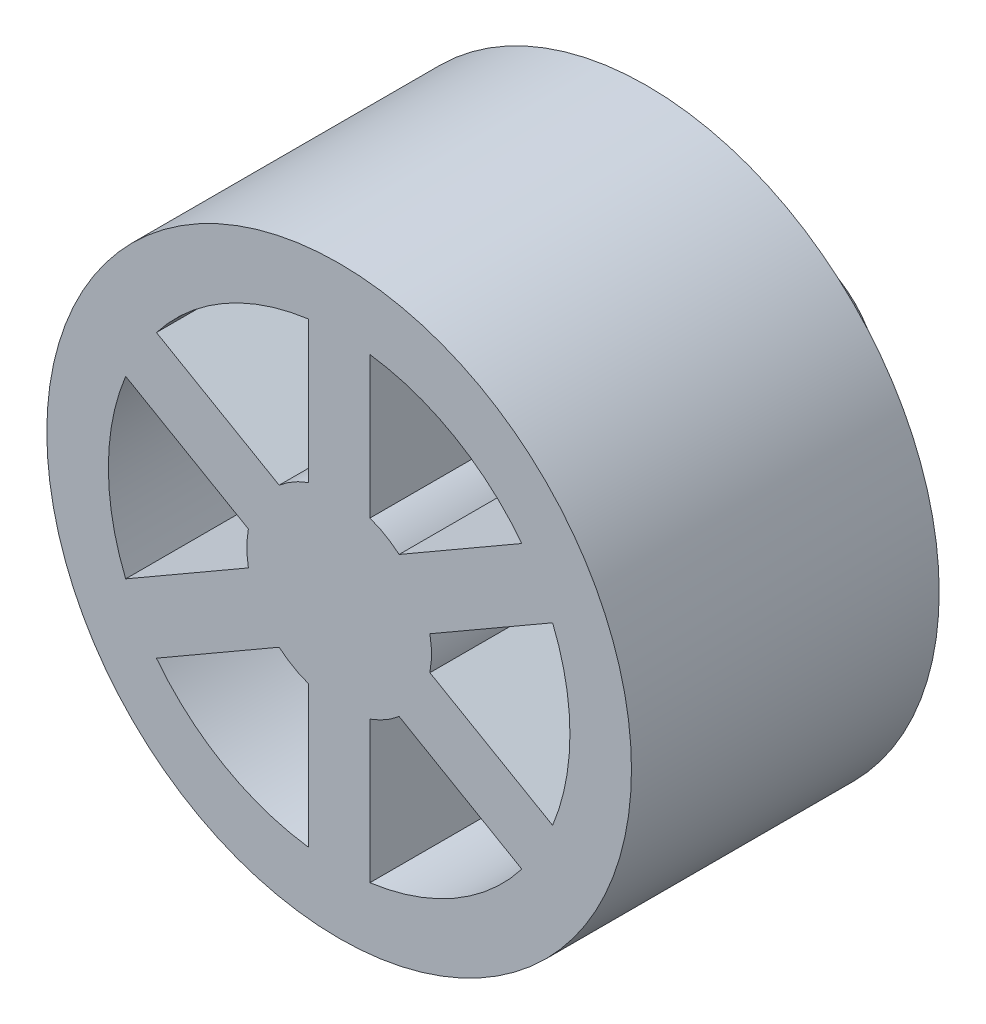
SolidWorks part; units mm, degrees
ref_plane "Płaszczyzna przednia" through (0, 0, 0) normal (0, 0, 1) x (1, 0, 0)
ref_plane "Płaszczyzna górna" through (0, 0, 0) normal (0, 1, 0) x (1, 0, 0)
ref_plane "Płaszczyzna prawa" through (0, 0, 0) normal (1, 0, 0) x (0, 0, -1)
sketch "Szkic1" plane through (0, 0, 0) normal (0, 0, 1) x (1, 0, 0)
  line L0 (-5.9372, -4.5825) -> (-1, -1.7321)
  line L2 (1, -7.433) -> (1, -1.7321)
  line L4 (-1, -7.433) -> (-1, -1.7321)
  line L5 (0.9912, -7.4342) -> (0.3965, -2.9737) construction
  line L6 (0.9912, 7.4342) -> (0.3965, 2.9737) construction
  line L8 (-6.9372, -2.8505) -> (-2, 0)
  line L10 (-6.9372, 2.8505) -> (-2, 0)
  line L12 (-5.9372, 4.5825) -> (-1, 1.7321)
  line L14 (2, 0) -> (6.9372, -2.8505)
  line L15 (-0.3965, -2.9737) -> (-0.9912, -7.4342) construction
  line L19 (-0.3965, 2.9737) -> (-0.9912, 7.4342) construction
  line L21 (1, 1.7321) -> (5.9372, 4.5825)
  line L22 (1, 1.7321) -> (1, 7.433)
  line L23 (2, 0) -> (6.9372, 2.8505)
  line L24 (1, -1.7321) -> (5.9372, -4.5825)
  line L28 (-1, 1.7321) -> (-1, 7.433)
  circle A0 centre (0, 0) radius 3
  circle A1 centre (0, 0) radius 7.5
  circle A2 centre (0, 0) radius 9.5
  point P5 (0, 0)
  point P21 (0, 0)
  dimension "D1" = 6
  dimension "D2" = 15
  dimension "D3" = 2
  dimension "D5" = 3
extrude "Dodanie-wyciągnięcie1" add sketch "Szkic1" along normal blind 10
sketch "Szkic2" plane through (0, 0, 0) normal (0, 0, -1) x (-1, 0, 0)
  circle A0 centre (0, 0) radius 3
  dimension "D1" = 6
extrude "Dodanie-wyciągnięcie2" add sketch "Szkic2" along normal blind 3.1
sketch "Szkic9" plane through (0, 0, 0) normal (0, 1, 0) x (1, 0, 0)
  line L6 (-3, 3.1) -> (0, 3.1)
  line L7 (3, 3.1) -> (-3, 3.1) construction
  line L8 (0, 3.1) -> (0, 5)
  line L11 (-3, 3.1) -> (-3.3477, 3.1932)
  line L12 (-3.3477, 3.1932) -> (-3, 5)
  line L13 (-3, 5) -> (0, 5)
  line L14 (-3, 3.1) -> (-3, -10) construction
  dimension "D1" = 0.36
  dimension "D2" = 105
  dimension "D3" = 1.9
  dimension "D4" = 1.84
revolve "Obrót1" add sketch "Szkic9" angle 360 about L8
fillet "Zaokrąglenie1" radius 1 1 edges at (3, 0, -5)
sketch "Szkic10" plane through (0, 0, -5) normal (0, 0, -1) x (-1, 0, 0)
  line L0 (0, 0) -> (1.7353, 5.2723)
  line L1 (1.7353, 5.2723) -> (-1.7337, 5.2723)
  line L2 (-1.7337, 5.2723) -> (0, 0)
  line L3 (0, 0) -> (5.2723, -1.7353)
  line L4 (5.2723, -1.7353) -> (5.2723, 1.7337)
  line L5 (5.2723, 1.7337) -> (0, 0)
  line L6 (0, 0) -> (-1.7353, -5.2723)
  line L7 (-1.7353, -5.2723) -> (1.7337, -5.2723)
  line L8 (1.7337, -5.2723) -> (0, 0)
  line L9 (0, 0) -> (-5.2723, 1.7353)
  line L10 (-5.2723, 1.7353) -> (-5.2723, -1.7337)
  line L11 (-5.2723, -1.7337) -> (0, 0)
  circle A0 centre (0, 0) radius 2
  point P13 (0, 0)
  circle M3 centre (0, 0) radius 2.1741
  dimension "D4" = 4
  dimension "D1" = 5.5505
  dimension "D2" = 5.55
  dimension "D3" = 4
extrude "Wytnij-wyciągnięcie2" cut sketch "Szkic10" against normal up to surface (5 mm away) contours L6 A0 L8 | L9 A0 L11 | L0 A0 L2 | L10 L11 L9 M3 | L1 L2 L0 M3 | L7 L8 L6 M3 | A0 L9 L11 M3 | A0 L0 L2 M3 | A0 L3 L5 M3 | A0 L6 L8 M3 | L3 A0 L5 | L4 L5 L3 M3 | L2 A0 L9 | L5 A0 L0 | L8 A0 L3 | L11 A0 L6
